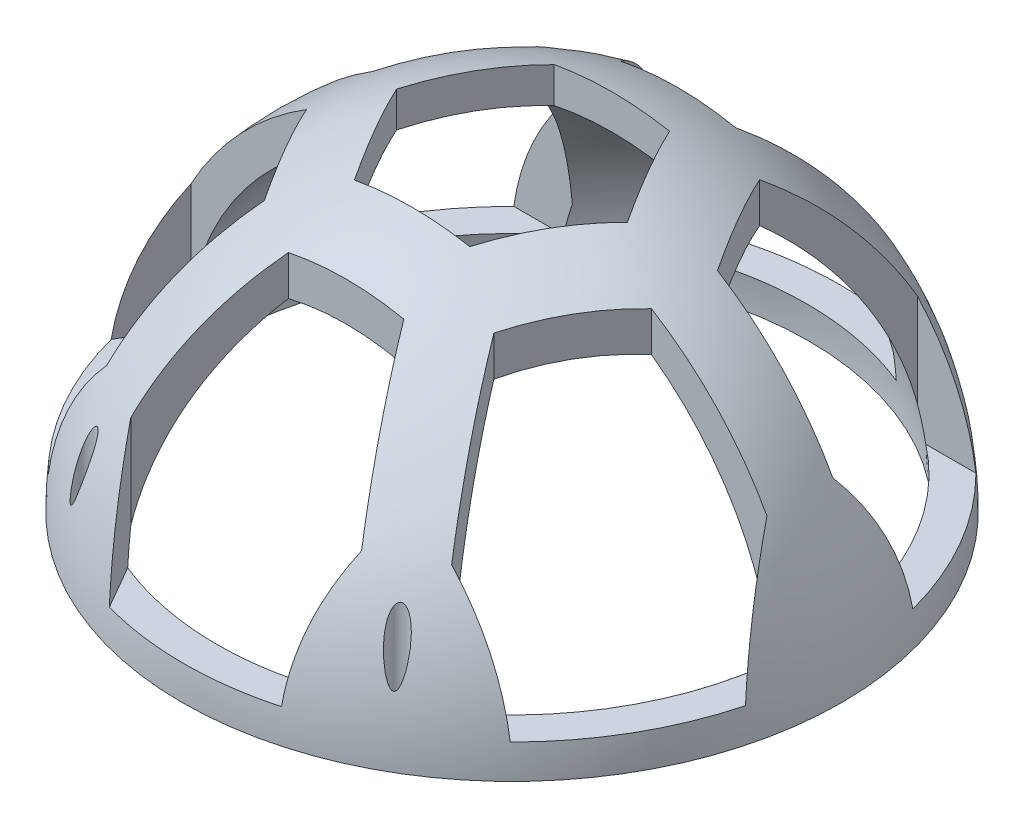
SolidWorks part; units mm, degrees
material "PLA"
ref_plane "Alzado" through (0, 0, 0) normal (0, 0, 1) x (1, 0, 0)
ref_plane "Planta" through (0, 0, 0) normal (0, 1, 0) x (1, 0, 0)
ref_plane "Vista lateral" through (0, 0, 0) normal (1, 0, 0) x (0, 0, -1)
sketch "Croquis1" plane through (0, 0, 0) normal (0, 1, 0) x (1, 0, 0)
  line L0 (0, -100) -> (0, 100) construction
  line L1 (0, 100) -> (0, -100) construction
  arc A0 (0, 100) -> (0, -100) centre (0, 0) cw
  point P4 (0, 0)
  dimension "D1" = 200
revolve "Revolución-Lámina1" add sketch "Croquis1" angle 180 about L1
sketch "Croquis2" plane through (0, 0, 0) normal (0, -1, 0) x (-1, 0, 0)
  line L79 (17.5, 30.3109) -> (-17.5, 30.3109)
  line L80 (-17.5, 30.3109) -> (-35, 0)
  line L81 (-35, 0) -> (-17.5, -30.3109)
  line L82 (-17.5, -30.3109) -> (17.5, -30.3109)
  line L83 (17.5, -30.3109) -> (35, 0)
  line L84 (35, 0) -> (17.5, 30.3109)
  line L85 (104.8205, 40.3109) -> (87.3205, 70.6218)
  line L86 (17.5, 110.9327) -> (-17.5, 110.9327)
  line L87 (-17.5, 110.9327) -> (-35, 80.6218)
  line L88 (-35, 80.6218) -> (-17.5, 50.3109)
  line L89 (-17.5, 50.3109) -> (17.5, 50.3109)
  line L90 (17.5, 50.3109) -> (35, 80.6218)
  line L91 (35, 80.6218) -> (17.5, 110.9327)
  line L92 (87.3205, 70.6218) -> (52.3205, 70.6218)
  line L93 (52.3205, 70.6218) -> (34.8205, 40.3109)
  line L94 (34.8205, 40.3109) -> (52.3205, 10)
  line L95 (52.3205, 10) -> (87.3205, 10)
  line L96 (87.3205, 10) -> (104.8205, 40.3109)
  line L97 (87.3205, -70.6218) -> (104.8205, -40.3109)
  line L98 (104.8205, -40.3109) -> (87.3205, -10)
  line L99 (87.3205, -10) -> (52.3205, -10)
  line L100 (52.3205, -10) -> (34.8205, -40.3109)
  line L101 (34.8205, -40.3109) -> (52.3205, -70.6218)
  line L102 (52.3205, -70.6218) -> (87.3205, -70.6218)
  line L103 (-17.5, -110.9327) -> (17.5, -110.9327)
  line L104 (17.5, -110.9327) -> (35, -80.6218)
  line L105 (35, -80.6218) -> (17.5, -50.3109)
  line L106 (17.5, -50.3109) -> (-17.5, -50.3109)
  line L107 (-17.5, -50.3109) -> (-35, -80.6218)
  line L108 (-35, -80.6218) -> (-17.5, -110.9327)
  line L109 (-104.8205, -40.3109) -> (-87.3205, -70.6218)
  line L110 (-87.3205, -70.6218) -> (-52.3205, -70.6218)
  line L111 (-52.3205, -70.6218) -> (-34.8205, -40.3109)
  line L112 (-34.8205, -40.3109) -> (-52.3205, -10)
  line L113 (-52.3205, -10) -> (-87.3205, -10)
  line L114 (-87.3205, -10) -> (-104.8205, -40.3109)
  line L115 (-87.3205, 70.6218) -> (-104.8205, 40.3109)
  line L116 (-104.8205, 40.3109) -> (-87.3205, 10)
  line L117 (-87.3205, 10) -> (-52.3205, 10)
  line L118 (-52.3205, 10) -> (-34.8205, 40.3109)
  line L119 (-34.8205, 40.3109) -> (-52.3205, 70.6218)
  line L120 (-52.3205, 70.6218) -> (-87.3205, 70.6218)
  circle A0 centre (0, 0) radius 30.3109 construction
  circle A1 centre (0, 80.6218) radius 30.3109 construction
  point P51 (0, 0)
  point P55 (0, 0)
  dimension "D1" = 35
  dimension "D2" = 6
  dimension "D3" = 35
  dimension "1.5" = 20
extrude "Cortar-Extruir1" cut sketch "Croquis2" against normal blind 100 from offset 10 offset against normal yes
ref_plane "Plano1" through (90, 0, 0) normal (-1, 0, 0) x (0, 0, 1)
sketch "Croquis4" plane through (90, 0, 0) normal (-1, 0, 0) x (0, 0, 1)
  line L1 (10, 5) -> (-10, 5)
  line L2 (10, 5) -> (10, -5)
  line L3 (10, -5) -> (-10, -5)
  line L4 (-10, 5) -> (-10, -5)
  line L5 (10, 5) -> (-10, -5) construction
  line L6 (10, -5) -> (-10, 5) construction
  point P0 (0, 0)
  dimension "D1" = 20
  dimension "D2" = 10
extrude "Cortar-Extruir2" cut sketch "Croquis4" against normal blind 4 and the other way blind 184
ref_plane "Plano2" through (0, 20, 0) normal (0, -1, 0) x (-1, 0, 0)
sketch "Croquis5" plane through (0, 20, 0) normal (0, -1, 0) x (-1, 0, 0)
  line L0 (-8.2837, 0) -> (11.3518, 0) construction
  line L1 (0, -11.5052) -> (0, 8.7439) construction
  line L2 (0, 0) -> (47.5, 82.2724) construction
  line L3 (0, 0) -> (47.5, -82.2724) construction
  line L4 (0, 0) -> (-47.5, -82.2724) construction
  line L5 (0, 0) -> (-47.5, 82.2724) construction
  circle A0 centre (-47.5, 82.2724) radius 3
  circle A1 centre (-47.5, -82.2724) radius 3
  circle A2 centre (47.5, -82.2724) radius 3
  circle A3 centre (47.5, 82.2724) radius 3
  dimension "D3" = 6
  dimension "D1" = 30
  dimension "D2" = 95
extrude "Cortar-Extruir3" cut sketch "Croquis5" along normal blind 15 and the other way blind 30
hole_wizard "Taladro roscado M4x0.71" positions "Croquis3D1" profile "Croquis8" tap size "M4x0.7" standard "Ansi Metric"
sketch3d "Croquis3D1"
  line L0 (47.5, 39.1918, 82.2724) -> (47.5, 5, 82.2724) construction
  line L1 (47.5, 39.1918, -82.2724) -> (47.5, 5, -82.2724) construction
  line L2 (-47.5, 39.1918, 82.2724) -> (-47.5, 5, 82.2724) construction
  line L3 (-47.5, 39.1918, -82.2724) -> (-47.5, 5, -82.2724) construction
  point P0 (47.5, 5, 82.2724)
  point P4 (47.5, 5, -82.2724)
  point P8 (-47.5, 5, 82.2724)
  point P12 (-47.5, 5, -82.2724)
sketch "Croquis8" plane through (47.5, 5, 82.2724) normal (1, 0, 0) x (0, 0, 1)
  line L0 (0, 0) -> (0, 8.9914)
  line L1 (0, 8.9914) -> (1.65, 8)
  line L2 (1.65, 8) -> (1.65, 0)
  line L5 (1.65, 0) -> (0, 0)
  line L10 (0, 8.9914) -> (-1.65, 8) construction
  line L11 (0, -6.35) -> (0, 107.95) construction
  dimension "Diámetro de perforador para roscar" = 3.3
  dimension "Profundidad de perforador para roscar" = 8
  dimension "Ángulo de perforador" = 118
cosmetic thread "Rosca de taladro1" parameters "D1"=8, "D2"=4
cosmetic thread "Rosca de taladro2" parameters "D1"=8, "D2"=4
cosmetic thread "Rosca de taladro3" parameters "D1"=8, "D2"=4
cosmetic thread "Rosca de taladro4" parameters "D1"=8, "D2"=4
